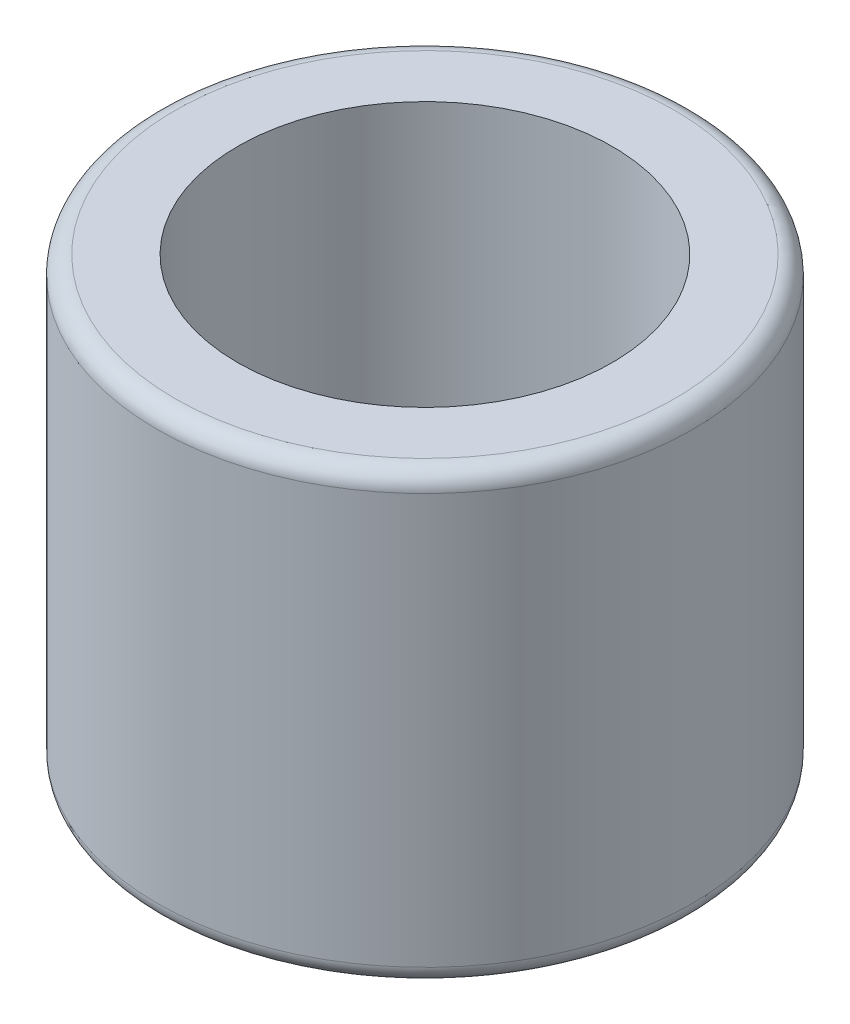
SolidWorks part; units mm, degrees
ref_plane "Front Plane" through (0, 0, 0) normal (0, 0, 1) x (1, 0, 0)
ref_plane "Top Plane" through (0, 0, 0) normal (0, 1, 0) x (1, 0, 0)
ref_plane "Right Plane" through (0, 0, 0) normal (1, 0, 0) x (0, 0, -1)
sketch "Sketch1" plane through (0, 0, 0) normal (0, 1, 0) x (1, 0, 0)
  circle A0 centre (0, 0) radius 3.81
  circle A1 centre (0, 0) radius 2.667
  point P5 (0, -0.1294)
  dimension "D1" = 5.334
  dimension "D2" = 7.62
extrude "Boss-Extrude1" add sketch "Sketch1" along normal blind 6.35
fillet "Fillet1" radius 0.254 2 edges at (0, 0, 3.81) (0, 6.35, 3.81)
